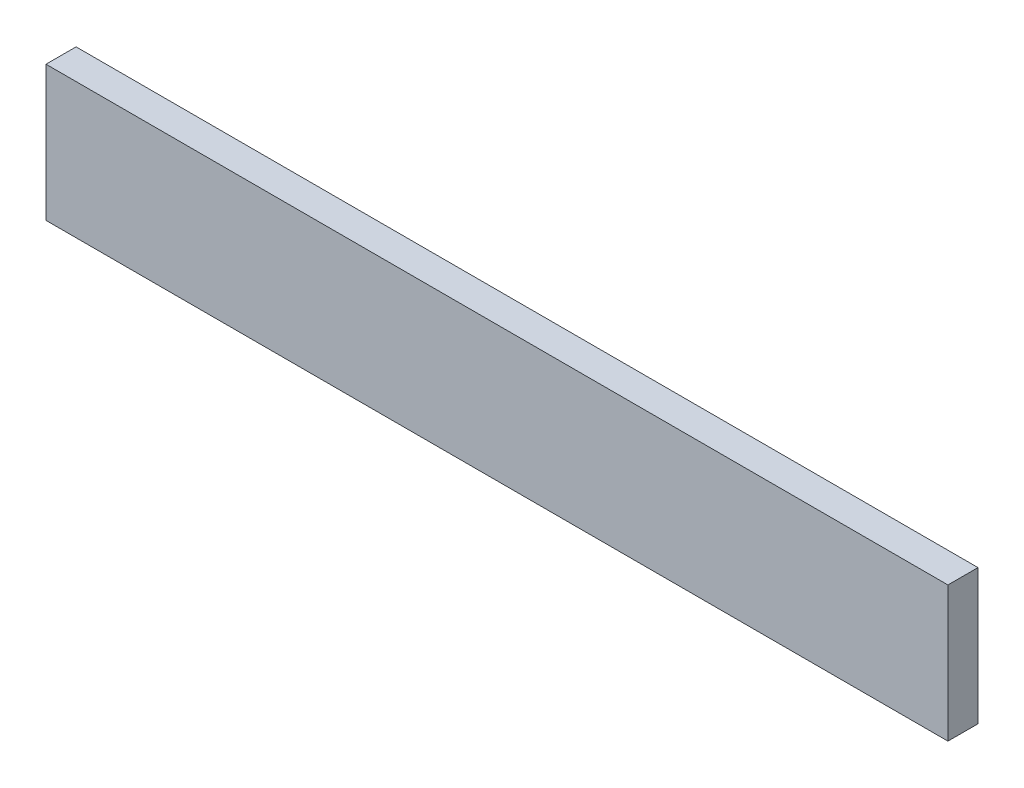
SolidWorks part; units mm, degrees
ref_plane "Front Plane" through (0, 0, 0) normal (0, 0, 1) x (1, 0, 0)
ref_plane "Top Plane" through (0, 0, 0) normal (0, 1, 0) x (1, 0, 0)
ref_plane "Right Plane" through (0, 0, 0) normal (1, 0, 0) x (0, 0, -1)
other "Graphic1"
sketch "Sketch3" plane through (0, 0, 0) normal (0, 0, 1) x (1, 0, 0)
  line L1 (-591.4494, 4426.9397) -> (-439.0494, 4426.9397)
  line L2 (-591.4494, 4426.9397) -> (-591.4494, 4404.0797)
  line L3 (-591.4494, 4404.0797) -> (-439.0494, 4404.0797)
  line L4 (-439.0494, 4426.9397) -> (-439.0494, 4404.0797)
  line L5 (-591.4494, 4426.9397) -> (-439.0494, 4404.0797) construction
  line L6 (-591.4494, 4404.0797) -> (-439.0494, 4426.9397) construction
  point P0 (-515.2494, 4415.5097)
  dimension "D1" = 22.86
  dimension "D2" = 152.4
extrude "Boss-Extrude4" add sketch "Sketch3" along normal blind 5.08
